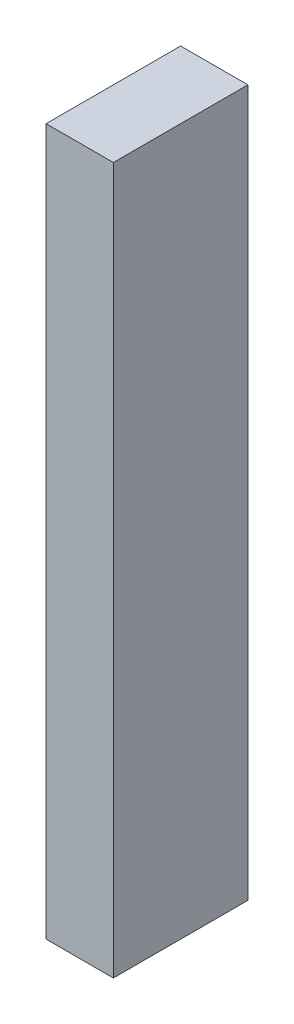
SolidWorks part; units mm, degrees
material "Teak"
ref_plane "Front Plane" through (0, 0, 0) normal (0, 0, 1) x (1, 0, 0)
ref_plane "Top Plane" through (0, 0, 0) normal (0, 1, 0) x (1, 0, 0)
ref_plane "Right Plane" through (0, 0, 0) normal (1, 0, 0) x (0, 0, -1)
sketch "Sketch1" plane through (0, 0, 0) normal (0, 1, 0) x (1, 0, 0)
  line L1 (0, 0) -> (50.8, 0)
  line L2 (0, 0) -> (0, 101.6)
  line L3 (0, 101.6) -> (50.8, 101.6)
  line L4 (50.8, 0) -> (50.8, 101.6)
  dimension "D1" = 101.6
  dimension "D2" = 50.8
extrude "Boss-Extrude1" add sketch "Sketch1" along normal blind 533.4
